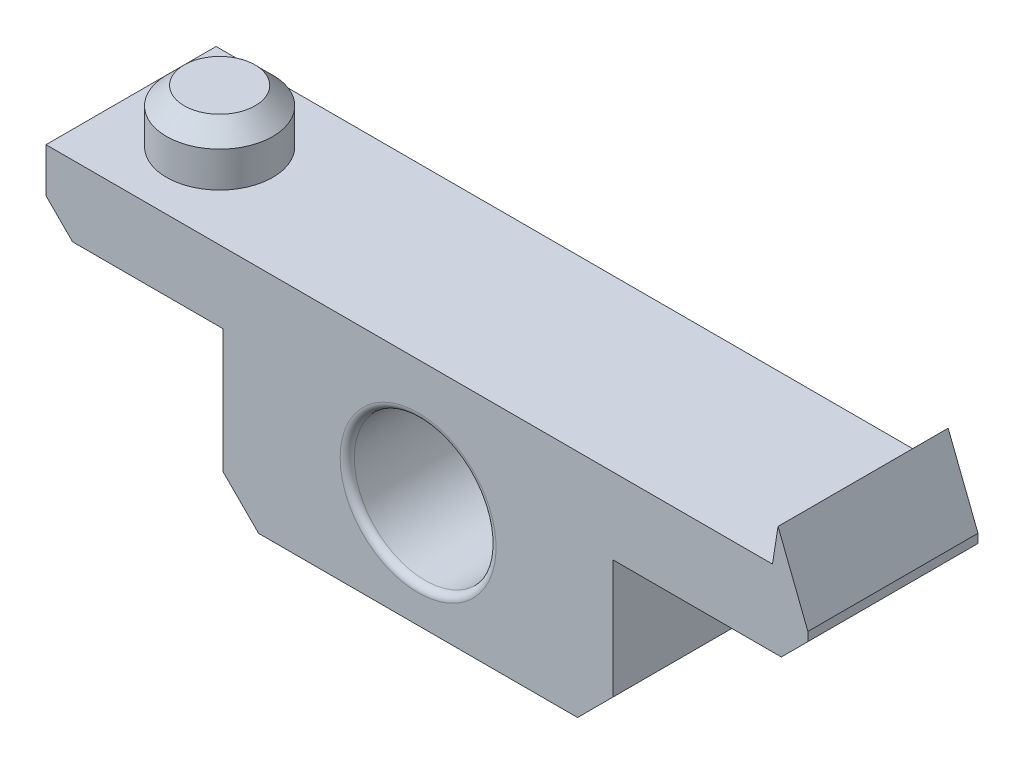
SolidWorks part; units mm, degrees
ref_plane "정면" through (0, 0, 0) normal (0, 0, 1) x (1, 0, 0)
ref_plane "윗면" through (0, 0, 0) normal (0, 1, 0) x (1, 0, 0)
ref_plane "우측면" through (0, 0, 0) normal (1, 0, 0) x (0, 0, -1)
sketch "스케치1" plane through (0, 0, 0) normal (0, 0, 1) x (1, 0, 0)
  line L0 (0, 0) -> (20.5, 0)
  line L2 (20.6573, 1) -> (21.5, -1.1461)
  line L3 (21.5, -1.1461) -> (21.5, -2.1461)
  line L4 (21.5, -2.1461) -> (16, -2.1461)
  line L5 (16, -2.1461) -> (16, -6.5)
  line L6 (16, -6.5) -> (5, -6.5)
  line L7 (5, -6.5) -> (5, -2)
  line L8 (5, -2) -> (0, -2)
  line L9 (0, -2) -> (0, 0)
  line L10 (20.5, 0) -> (20.6573, 1)
  dimension "D1" = 21.5
  dimension "D2" = 6.5
  dimension "D3" = 1
  dimension "D4" = 2
  dimension "D5" = 11
  dimension "D6" = 5
  dimension "D8" = 1
extrude "보스-돌출1" add sketch "스케치1" along normal blind 4.8
sketch "스케치2" plane through (0, 0, 4.8) normal (0, 0, 1) x (1, 0, 0)
  line L0 (5, -6.5) -> (16, -6.5) construction
  line L1 (5, -2) -> (5, -6.5) construction
  circle A0 centre (10.5, -3.5) radius 2
  dimension "D1" = 4
  dimension "D2" = 3
  dimension "D3" = 5.5
extrude "컷-돌출1" cut sketch "스케치2" against normal blind 10
chamfer "모따기1" distance 1 angle 45 2 edges at (16, -6.5, 2.4) (5, -6.5, 2.4)
chamfer "모따기2" distance 0.75 angle 45 2 edges at (21.5, -2.1461, 2.4) (0, -2, 2.4)
sketch "스케치3" plane through (0, 0, 0) normal (0, 1, 0) x (1, 0, 0)
  line L0 (0, -4.8) -> (0, 0) construction
  circle A0 centre (2.5, -2.4) radius 1.5
  dimension "D1" = 3
  dimension "D2" = 2.5
extrude "보스-돌출2" add sketch "스케치3" along normal blind 1.5
chamfer "모따기3" distance 0.5 angle 45 1 edges at (2.5, 1.5, 3.9)
fillet "필렛2" radius 0.2 2 edges at (8.5, -3.5, 0) (12.5, -3.5, 4.8)
